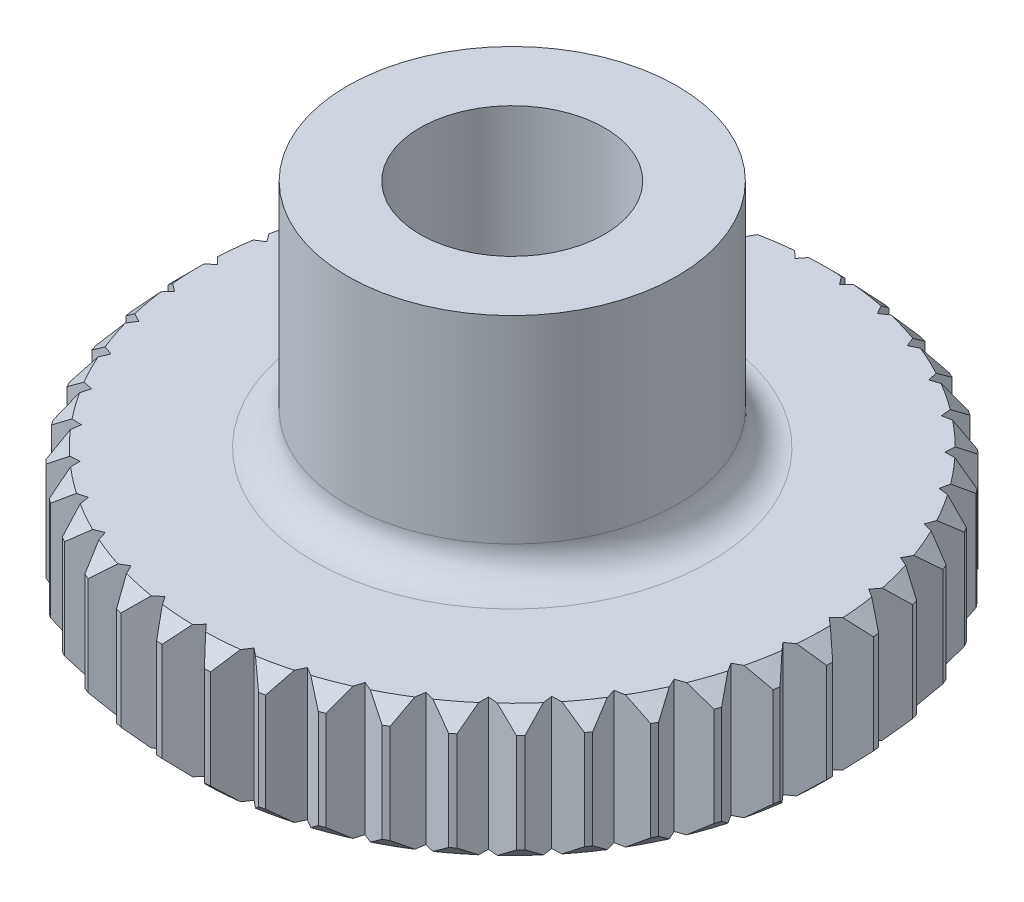
SolidWorks part; units mm, degrees
ref_plane "Přední rovina" through (0, 0, 0) normal (0, 0, 1) x (1, 0, 0)
ref_plane "Vrchní rovina" through (0, 0, 0) normal (0, 1, 0) x (1, 0, 0)
ref_plane "Pravá rovina" through (0, 0, 0) normal (1, 0, 0) x (0, 0, -1)
sketch "Skica1" plane through (0, 0, 0) normal (0, 1, 0) x (1, 0, 0)
  circle A0 centre (0, 0) radius 10
  dimension "D" = 20
extrude "Vysunout1" add sketch "Skica1" along normal blind 4
chamfer "Zkosit1" distance 0.5 angle 45 2 edges at (0, 0, 10) (0, 4, 10)
sketch "Skica2" plane through (0, 0, 0) normal (0, -1, 0) x (1, 0, 0)
  line L0 (0, 0) -> (0, 10) construction
  line L1 (0.6407, 9.9795) -> (0, 9.2803)
  line L2 (0, 9.2803) -> (-0.6407, 9.9795)
  circle A0 centre (0, 0) radius 10 construction
  arc A1 (0.6407, 9.9795) -> (-0.6407, 9.9795) centre (0, 0) ccw
  dimension "D1" = 1.2823
  dimension "D2" = 85
extrude "Odebrat vysunutím1" cut sketch "Skica2" against normal through all
pattern_circular "Kruhové pole1" count 43 over 360 about axis through (0, 0, 0) along (0, 1, 0) of "Odebrat vysunutím1"
sketch "Skica3" plane through (0, 0, 0) normal (0, -1, 0) x (1, 0, 0)
  circle A0 centre (0, 0) radius 5
  dimension "D1" = 10
extrude "Vysunout2" add sketch "Skica3" against normal blind 11
fillet "Zaoblit1" radius 1 1 edges at (0, 4, 5)
sketch "Skica4" plane through (0, 0, 0) normal (0, -1, 0) x (1, 0, 0)
  circle A0 centre (0, 0) radius 2.125
  dimension "D1" = 4.25
extrude "Odebrat vysunutím2" cut sketch "Skica4" against normal through all
cosmetic thread "Kosmetický závit1" parameters "M"=5
sketch "Skica5" plane through (0, 0, 0) normal (1, 0, 0) x (0, 0, -1)
  line L0 (-2.8, 11) -> (-2.8, 6.5)
  line L1 (5, 11) -> (-5, 11) construction
  line L2 (-2.8, 6.5) -> (0, 4.8834)
  line L3 (0, 11) -> (0, 0) construction
  line L4 (0, 4.8834) -> (0, 11)
  line L5 (0, 11) -> (-2.8, 11)
  line L6 (0, 11) -> (0, 0) construction
  dimension "d3" = 5.6
  dimension "D2" = 60
  dimension "p" = 4.5
revolve "Odebrat otočením1" cut sketch "Skica5" angle 360 about L6
equation "\"D1@Skica4\" = 0.85 * \"M@Kosmetický závit1\""
